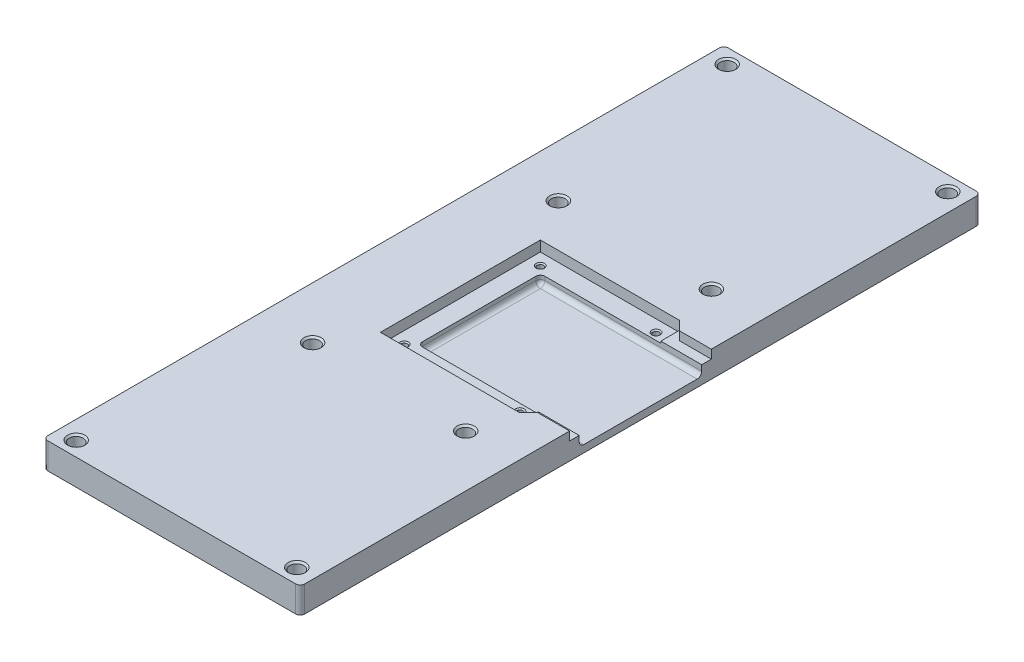
SolidWorks part; units mm, degrees
ref_plane "Front Plane" through (0, 0, 0) normal (0, 0, 1) x (1, 0, 0)
ref_plane "Top Plane" through (0, 0, 0) normal (0, 1, 0) x (1, 0, 0)
ref_plane "Right Plane" through (0, 0, 0) normal (1, 0, 0) x (0, 0, -1)
sketch "Sketch1" plane through (0, 0, 0) normal (0, 1, 0) x (1, 0, 0)
  line L0 (0, -135) -> (0, 135) construction
  line L1 (56.625, 135) -> (-56.625, 135) construction
  line L2 (-56.625, 135) -> (-56.625, -135)
  line L3 (-56.625, 0) -> (56.625, 0) construction
  line L4 (-56.625, 135) -> (-56.625, 148)
  line L5 (-54.625, 150) -> (54.625, 150)
  line L6 (0, 150) -> (0, 135) construction
  line L7 (56.625, 135) -> (56.625, 148)
  line L8 (56.625, 135) -> (56.625, -135)
  line L9 (0, -150) -> (0, -135) construction
  line L10 (56.625, -135) -> (-56.625, -135) construction
  line L11 (56.625, -135) -> (56.625, -148)
  line L12 (-54.625, -150) -> (54.625, -150)
  line L13 (-56.625, -135) -> (-56.625, -148)
  line L14 (-56.625, 138) -> (56.625, 138) construction
  circle A1 centre (-48.625, 143.5) radius 3.075 construction
  circle A2 centre (48.625, 143.5) radius 3.075 construction
  circle A5 centre (48.625, -143.5) radius 3.075 construction
  circle A6 centre (-48.625, -143.5) radius 3.075 construction
  arc A8 (-54.625, -150) -> (-56.625, -148) centre (-54.625, -148) cw
  arc A9 (56.625, -148) -> (54.625, -150) centre (54.625, -148) cw
  arc A10 (56.625, 148) -> (54.625, 150) centre (54.625, 148) ccw
  arc A11 (-56.625, 148) -> (-54.625, 150) centre (-54.625, 148) cw
  circle A12 centre (-33.75, 54.175) radius 3.075 construction
  circle A13 centre (33.75, 54.175) radius 3.075 construction
  circle A14 centre (33.75, -54.175) radius 3.075 construction
  circle A15 centre (-33.75, -54.175) radius 3.075 construction
  point P24 (0, 0)
  point P36 (-56.625, -150)
  point P39 (56.625, -150)
  point P42 (56.625, 150)
  point P45 (-56.625, 150)
  dimension "D5" = 54.175
  dimension "D10" = 2
  dimension "D3" = 6.15
  dimension "D1" = 56.625
  dimension "D2" = 135
  dimension "D4" = 6.5
  dimension "D6" = 8
  dimension "D7" = 8.5
  dimension "D8" = 12
  dimension "D9" = 3
  dimension "D11" = 150
  dimension "D12" = 33.75
extrude "Boss-Extrude1" add sketch "Sketch1" along normal blind 11.5
sketch "Sketch3" plane through (0, 11.5, 0) normal (0, 1, 0) x (1, 0, 0)
  line L0 (0, 0) -> (-56.625, 0) construction
  line L1 (-56.625, 148) -> (-56.625, -148) construction
  line L2 (0, 0) -> (0, 150) construction
  line L3 (54.625, 150) -> (-54.625, 150) construction
  line L4 (3.96, -16.3) -> (3.96, 16.3)
  line L5 (-2.46, -17.8) -> (2.46, -17.8)
  line L6 (-3.96, 16.3) -> (-3.96, -16.3)
  line L7 (2.46, 17.8) -> (-2.46, 17.8)
  line L8 (0, 17.8) -> (0, -17.8) construction
  line L9 (13.25, 0) -> (0, 0) construction
  line L10 (16.15, 10.025) -> (10.35, 10.025)
  line L11 (16.15, 10.025) -> (16.15, -10.025)
  line L12 (16.15, -10.025) -> (10.35, -10.025)
  line L13 (10.35, 10.025) -> (10.35, -10.025)
  line L14 (16.15, 10.025) -> (10.35, -10.025) construction
  line L15 (16.15, -10.025) -> (10.35, 10.025) construction
  line L16 (13.25, 0) -> (13.25, 10.025) construction
  line L17 (-16.15, 10.025) -> (-16.15, -10.025)
  line L18 (-16.15, -10.025) -> (-10.35, -10.025)
  line L23 (-16.15, 10.025) -> (-10.35, 10.025)
  line L24 (-10.35, 10.025) -> (-10.35, -10.025)
  arc A0 (-2.46, 17.8) -> (-3.96, 16.3) centre (-2.46, 16.3) ccw
  arc A1 (3.96, 16.3) -> (2.46, 17.8) centre (2.46, 16.3) ccw
  arc A2 (2.46, -17.8) -> (3.96, -16.3) centre (2.46, -16.3) ccw
  arc A3 (-3.96, -16.3) -> (-2.46, -17.8) centre (-2.46, -16.3) ccw
  point P9 (0, 0)
  point P23 (0, 0)
  dimension "D2" = 1.5
  dimension "D1" = 35.6
  dimension "D3" = 7.92
  dimension "D4" = 20.05
  dimension "D5" = 5.8
  dimension "D6" = 13.25
sketch "Sketch4" plane through (0, 11.5, 0) normal (0, 1, 0) x (1, 0, 0)
  circle A0 centre (-48.625, -143.5) radius 3.075 construction
  circle A1 centre (48.625, -143.5) radius 3.075 construction
  circle A2 centre (48.625, 143.5) radius 3.075 construction
  circle A5 centre (-48.625, 143.5) radius 3.075 construction
  circle A8 centre (-48.625, -143.5) radius 3.075
  circle A9 centre (48.625, -143.5) radius 3.075
  circle A10 centre (48.625, 143.5) radius 3.075
  circle A13 centre (-48.625, 143.5) radius 3.075
  circle A18 centre (-33.75, -54.175) radius 3.075 construction
  circle A19 centre (33.75, -54.175) radius 3.075 construction
  circle A20 centre (33.75, 54.175) radius 3.075 construction
  circle A21 centre (-33.75, 54.175) radius 3.075 construction
  circle A22 centre (-33.75, -54.175) radius 3.075
  circle A23 centre (33.75, -54.175) radius 3.075
  circle A24 centre (33.75, 54.175) radius 3.075
  circle A25 centre (-33.75, 54.175) radius 3.075
extrude "Cut-Extrude1" cut sketch "Sketch4" against normal blind 6
sketch "Sketch21" plane through (0, 11.5, 0) normal (0, 1, 0) x (1, 0, 0)
  line L0 (38.5, 35) -> (-22.5, 35) construction
  line L1 (38.5, 35) -> (42.5, 31) construction
  line L2 (-22.5, 35) -> (-22.5, -35) construction
  line L3 (-22.5, 0) -> (0, 0) construction
  line L4 (0, 0) -> (38.5, 0) construction
  line L5 (38.5, -35) -> (38.5, 35) construction
  line L6 (38.5, -35) -> (-22.5, -35) construction
  line L7 (42.5, 31) -> (56.625, 31) construction
  line L8 (56.625, -148) -> (56.625, 148) construction
  line L9 (56.625, 31) -> (56.625, -31)
  line L10 (56.625, 0) -> (38.5, 0) construction
  line L11 (42.5, -31) -> (56.625, -31) construction
  line L12 (38.5, -35) -> (42.5, -31) construction
  line L13 (42.6036, 31.25) -> (56.625, 31.25)
  line L14 (38.6036, 35.25) -> (42.6036, 31.25)
  line L15 (38.6036, 35.25) -> (-22.75, 35.25)
  line L16 (-22.75, 35.25) -> (-22.75, -35.25)
  line L17 (38.6036, -35.25) -> (-22.75, -35.25)
  line L18 (38.6036, -35.25) -> (42.6036, -31.25)
  line L19 (42.6036, -31.25) -> (56.625, -31.25)
  line L20 (56.625, -31.25) -> (56.625, -31)
  line L21 (56.625, 31) -> (56.625, 31.25)
  circle A0 centre (-17.5, 30) radius 1.6 construction
  circle A1 centre (33.5, 30) radius 1.6 construction
  circle A2 centre (33.5, -30) radius 1.6 construction
  circle A3 centre (-17.5, -30) radius 1.6 construction
  dimension "D8" = 3.2
  dimension "D1" = 22.5
  dimension "D2" = 61
  dimension "D3" = 35
  dimension "D4" = 5
  dimension "D5" = 5
  dimension "D6" = 5
  dimension "D7" = 5
  dimension "D9" = 45
  dimension "D10" = 4
  dimension "D12" = 14.125
  dimension "D11" = 0.25
extrude "Cut-Extrude6" cut sketch "Sketch21" against normal blind 4.6
sketch "Sketch24" plane through (0, 6.9, 0) normal (0, 1, 0) x (1, 0, 0)
  line L0 (56.625, 27) -> (-14.5, 27)
  line L2 (-14.5, 27) -> (-14.5, -27)
  line L3 (-14.5, -27) -> (56.625, -27)
  line L4 (56.625, -27) -> (56.625, 27)
  line L8 (38.5, 35) -> (-22.5, 35) construction
  line L10 (-22.5, 35) -> (-22.5, -35) construction
  line L11 (38.5, -35) -> (-22.5, -35) construction
  line L12 (56.625, -31.25) -> (56.625, 31.25) construction
  dimension "D1" = 8
  dimension "D2" = 8
  dimension "D3" = 8
extrude "Cut-Extrude3" cut sketch "Sketch24" against normal blind 3.7 and the other way through all
sketch "Sketch25" plane through (0, 6.9, 0) normal (0, 1, 0) x (1, 0, 0)
  circle A0 centre (33.5, 30) radius 1.35
  circle A1 centre (-17.5, 30) radius 1.35
  circle A2 centre (33.5, -30) radius 1.35
  circle A3 centre (-17.5, -30) radius 1.35
  dimension "D1" = 2.7
extrude "Cut-Extrude4" cut sketch "Sketch25" against normal blind 5
chamfer "Chamfer4" distance 0.5 angle 45 4 edges at (-17.5, 6.9, 31.35) (33.5, 6.9, 31.35) (33.5, 6.9, -28.65) (-17.5, 6.9, -28.65)
fillet "Fillet1" radius 2 5 edges at (21.0625, 3.2, 27) (-14.5, 5.05, 27) (-14.5, 5.05, -27) (-14.5, 3.2, 0) (21.0625, 3.2, -27)
sketch "Sketch26" plane through (0, 6.9, 0) normal (0, 1, 0) x (1, 0, 0)
  line L0 (0, 0) -> (56.625, 0) construction
  line L1 (56.625, -25) -> (56.625, 25) construction
  line L2 (38.6036, 35.25) -> (38.6036, 27)
  line L3 (56.625, 27) -> (-12.5, 27) construction
  line L4 (38.6036, 27) -> (56.625, 27)
  line L5 (56.625, 27) -> (56.625, 31.25)
  line L6 (56.625, 31.25) -> (42.6036, 31.25)
  line L7 (42.6036, 31.25) -> (38.6036, 35.25)
  line L8 (42.6036, -31.25) -> (38.6036, -35.25)
  line L9 (56.625, -31.25) -> (42.6036, -31.25)
  line L10 (56.625, -27) -> (56.625, -31.25)
  line L11 (38.6036, -27) -> (56.625, -27)
  line L12 (38.6036, -35.25) -> (38.6036, -27)
extrude "Boss-Extrude2" add sketch "Sketch26" along normal blind 0.8
chamfer "Chamfer5" distance 0.75 angle 45 8 edges at (48.625, 11.5, 146.575) (-48.625, 11.5, 146.575) (-48.625, 11.5, -140.425) (48.625, 11.5, -140.425) (-33.75, 11.5, 57.25) (33.75, 11.5, 57.25) (33.75, 11.5, -51.1) (-33.75, 11.5, -51.1)
equation "\"D5@Sketch21\"=\"D4@Sketch21\""
equation "\"D6@Sketch21\"=\"D4@Sketch21\""
equation "\"D7@Sketch21\"=\"D4@Sketch21\""
equation "\"D2@Sketch24\"=\"D1@Sketch24\""
equation "\"D3@Sketch24\"=\"D1@Sketch24\""
